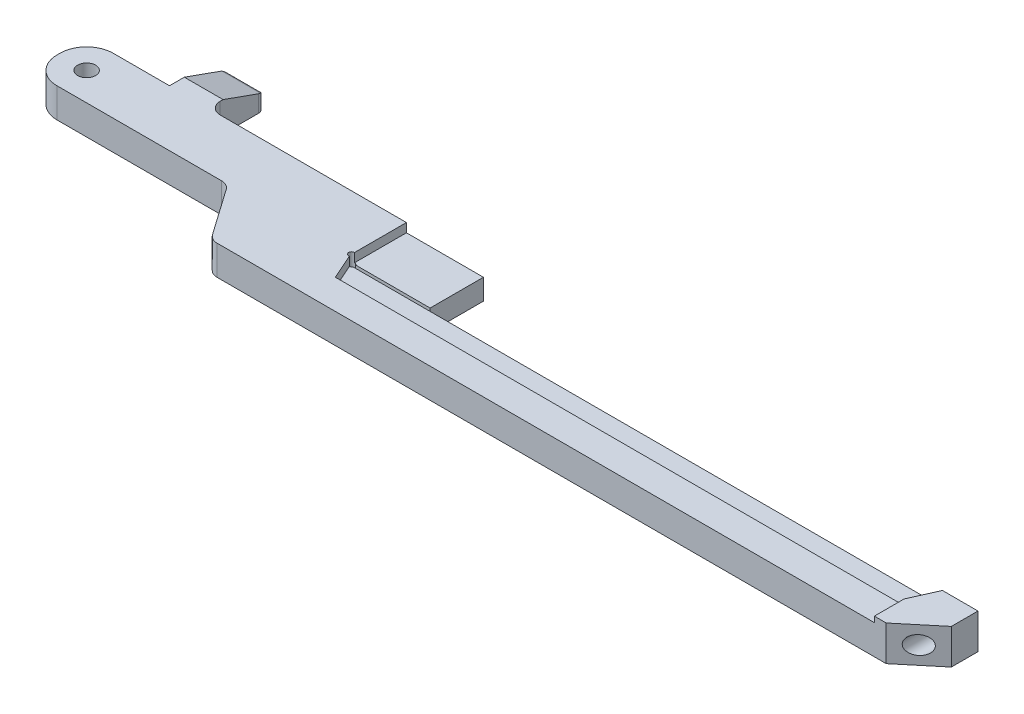
SolidWorks part; units mm, degrees
ref_plane "前视基准面" through (0, 0, 0) normal (0, 0, 1) x (1, 0, 0)
ref_plane "上视基准面" through (0, 0, 0) normal (0, 1, 0) x (1, 0, 0)
ref_plane "右视基准面" through (0, 0, 0) normal (1, 0, 0) x (0, 0, -1)
sketch "草图1" plane through (0, 0, 0) normal (0, 1, 0) x (1, 0, 0)
  line L0 (0, -4.75) -> (4.75, -4.75) construction
  line L1 (0, 0) -> (14, 0) construction
  line L2 (0, 0) -> (0, -9.5) construction
  line L3 (0, -9.5) -> (54.3333, -9.5) construction
  line L5 (0, -4.75) -> (30, -4.75) construction
  line L6 (30, -4.75) -> (75, -4.75) construction
  line L7 (75, -4.75) -> (75, -9.5) construction
  line L8 (75, -9.5) -> (75, -14) construction
  line L9 (75, -14) -> (75, -19) construction
  line L10 (75, -19) -> (70, -19)
  line L11 (75, -4.75) -> (55, -4.75) construction
  line L12 (58.3333, -9.5) -> (65, -19) construction
  line L13 (75, -19) -> (175, -19)
  line L14 (175, -19) -> (180, -19) construction
  line L15 (180, -19) -> (180, -9.5) construction
  line L16 (75, -9.5) -> (75, -9) construction
  line L17 (75.9682, -9) -> (88, -9)
  line L18 (88, -9) -> (88, 0)
  line L19 (75.9682, -9.5) -> (181, -9.5)
  line L20 (175, -19) -> (181, -9.5) construction
  line L21 (181, -9.5) -> (181, -14)
  line L22 (181, -14) -> (175, -19)
  line L23 (75.9682, -9) -> (75.433, -9)
  line L24 (75.9682, -9.5) -> (75.433, -9.5)
  line L25 (0, 0) -> (0, 9.5) construction
  line L26 (0, 9.5) -> (14, 9.5) construction
  line L27 (14, 6.5) -> (14, 0) construction
  line L28 (17, 9.5) -> (17.55, 9.5) construction
  line L29 (20.55, 6.5) -> (20.55, 0) construction
  line L30 (20.55, 0) -> (88, 0) construction
  line L31 (30, 0) -> (30, -9.5) construction
  line L32 (30, -4.75) -> (34.75, -4.75) construction
  line L33 (44, 0) -> (50.55, 0)
  line L34 (35, 0) -> (30, 0)
  line L35 (35, 9.5) -> (41.55, 9.5)
  line L36 (35, 9.5) -> (35, 0)
  line L37 (41.55, 9.5) -> (41.55, 0)
  line L38 (30, -9.5) -> (54.3333, -9.5)
  line L39 (88, 0) -> (50.55, 0)
  line L41 (63.3333, -9.5) -> (70, -19) construction
  line L42 (44, 0) -> (41.55, 0)
  line L43 (30, -9.5) -> (21, -9.5)
  line L44 (21, -9.5) -> (21, 0)
  line L45 (21, 0) -> (30, 0)
  line L46 (70, -19) -> (61, -19)
  line L47 (61, -19) -> (54.3333, -9.5)
  circle A0 centre (4.75, -4.75) radius 1.525 construction
  arc A3 (75.433, -9) -> (75.433, -9.5) centre (75, -9.25) ccw
  arc A4 (17.55, 9.5) -> (20.55, 6.5) centre (17.55, 6.5) cw construction
  arc A5 (14, 6.5) -> (17, 9.5) centre (17, 6.5) cw construction
  circle A6 centre (25.75, -4.75) radius 1.525
  point P34 (20.55, 9.5)
  dimension "D3" = 4.75
  dimension "D12" = 13
  dimension "D13" = 14
  dimension "D16" = 3
  dimension "D17" = 160
  dimension "D1" = 9.5
  dimension "D2" = 181
  dimension "D4" = 30
  dimension "D5" = 45
  dimension "D6" = 4.5
  dimension "D7" = 5
  dimension "D8" = 20
  dimension "D9" = 10
  dimension "D10" = 100
  dimension "D11" = 5
  dimension "D14" = 9.5
  dimension "D15" = 6.55
  dimension "D19" = 6.55
extrude "凸台-拉伸1" add sketch "草图1" along normal blind 5
sketch "草图2" plane through (0, 0, 0) normal (0, 1, 0) x (1, 0, 0)
  line L0 (75, -9) -> (75, 0)
  line L1 (75.433, -9) -> (75, -9)
  line L2 (75.433, -9.5) -> (181, -9.5) construction
  line L3 (75.433, -9.5) -> (175, -9.5)
  line L7 (75.433, -9.5) -> (75, -9.5)
  line L9 (75.433, -9) -> (88, -9)
  line L10 (88, -9) -> (88, 0)
  line L11 (35, 0) -> (21, 0)
  line L13 (88, 0) -> (41.55, 0)
  line L15 (61, -19) -> (175, -19)
  line L16 (175, -19) -> (181, -14)
  line L17 (181, -9.5) -> (75.433, -9.5)
  line L18 (75.433, -9) -> (88, -9)
  line L19 (88, -9) -> (88, 0)
  line L29 (173, -14) -> (175, -9.5)
  line L30 (173, -14) -> (77, -14)
  line L32 (77, -14) -> (75, -9.5)
  line L33 (75, 0) -> (88, 0)
  line L44 (181, -14) -> (181, -9.5)
  line L47 (21, 0) -> (21, -9.5)
  line L49 (41.55, 0) -> (41.55, 9.5)
  line L51 (41.55, 9.5) -> (35, 9.5)
  line L52 (21, -9.5) -> (54.3333, -9.5)
  line L53 (35, 9.5) -> (35, 0)
  line L55 (54.3333, -9.5) -> (61, -19)
  arc A1 (75.433, -9) -> (75.433, -9.5) centre (75, -9.25) ccw
  dimension "D1" = 0
extrude "切除-拉伸1" cut sketch "草图2" along normal through all from offset 3.5
sketch "草图3" plane through (0, 0, 0) normal (0, 1, 0) x (1, 0, 0)
  circle A2 centre (25.75, -4.75) radius 3
extrude "切除-拉伸2" cut sketch "草图3" along normal blind 2
sketch "草图6" plane through (0, 0, 0) normal (0, 1, 0) x (1, 0, 0)
  line L1 (173, -14) -> (173, -19)
  line L2 (175, -19) -> (61, -19) construction
  line L3 (173, -19) -> (175, -19)
  line L10 (175, -9.5) -> (173, -14)
  line L15 (61, -19) -> (175, -19)
  line L16 (175, -19) -> (181, -14)
  line L17 (181, -14) -> (181, -9.5)
  line L18 (181, -9.5) -> (175, -9.5)
  line L22 (175, -9.5) -> (173, -14)
  line L23 (173, -14) -> (77, -14)
  line L28 (175, -19) -> (181, -14)
  line L29 (181, -14) -> (181, -9.5)
  line L30 (181, -9.5) -> (175, -9.5)
  line L37 (75, 0) -> (41.55, 0)
  line L39 (77, -14) -> (75.1061, -9.7386)
  line L41 (35, 0) -> (21, 0)
  line L47 (41.55, 0) -> (41.55, 9.5)
  line L48 (21, 0) -> (21, -9.5)
  line L49 (41.55, 9.5) -> (35, 9.5)
  line L51 (35, 9.5) -> (35, 0)
  line L52 (21, -9.5) -> (54.3333, -9.5)
  line L54 (54.3333, -9.5) -> (61, -19)
  line L58 (75, -8.75) -> (75, 0)
  arc A4 (75, -8.75) -> (75.1061, -9.7386) centre (75, -9.25) ccw
  dimension "D1" = 0
extrude "凸台-拉伸2" add sketch "草图6" along normal blind 5.95
sketch "草图7" plane through (0, 0, 0) normal (0, 0, 1) x (1, 0, 0)
  line L0 (181, 2.975) -> (178, 2.975) construction
  line L5 (75.433, 3.5) -> (75.433, 0)
  line L6 (181, 0) -> (181, 5.95)
  line L7 (75.433, 0) -> (181, 0)
  line L8 (175, 5.95) -> (175, 3.5)
  line L9 (181, 5.95) -> (175, 5.95)
  line L12 (181, 0) -> (181, 5.95) construction
  line L18 (175, 3.5) -> (75.433, 3.5)
  line L19 (181, 5.95) -> (175, 5.95) construction
  circle A0 centre (178, 2.975) radius 1.525
  dimension "D1" = 0
extrude "切除-拉伸3" cut sketch "草图7" along normal through all
fillet "圆角4" radius 4.5 2 edges at (21, 2.5, 9.5) (21, 2.5, 0)
sketch "草图8" plane through (0, 0, 0) normal (1, 0, 0) x (0, 0, -1)
  line L1 (2.5, 5) -> (9.5, 2.5)
  line L4 (0, 0) -> (9.5, 0)
  line L5 (0, 5) -> (0, 0)
  line L6 (9.5, 5) -> (0, 5)
  line L7 (9.5, 0) -> (9.5, 5)
  line L10 (9.5, 5) -> (2.5, 5)
  line L11 (9.5, 2.5) -> (9.5, 5)
  dimension "D1" = 0
extrude "切除-拉伸4" cut sketch "草图8" along normal through all
fillet "圆角5" radius 2 3 edges at (41.55, 2.5, 0) (54.3333, 2.5, 9.5) (61, 2.5, 19)
fillet "圆角6" radius 1 3 edges at (41.55, 1.25, -9.5) (35, 1.25, -9.5) (38.275, 2.5, -9.5)
